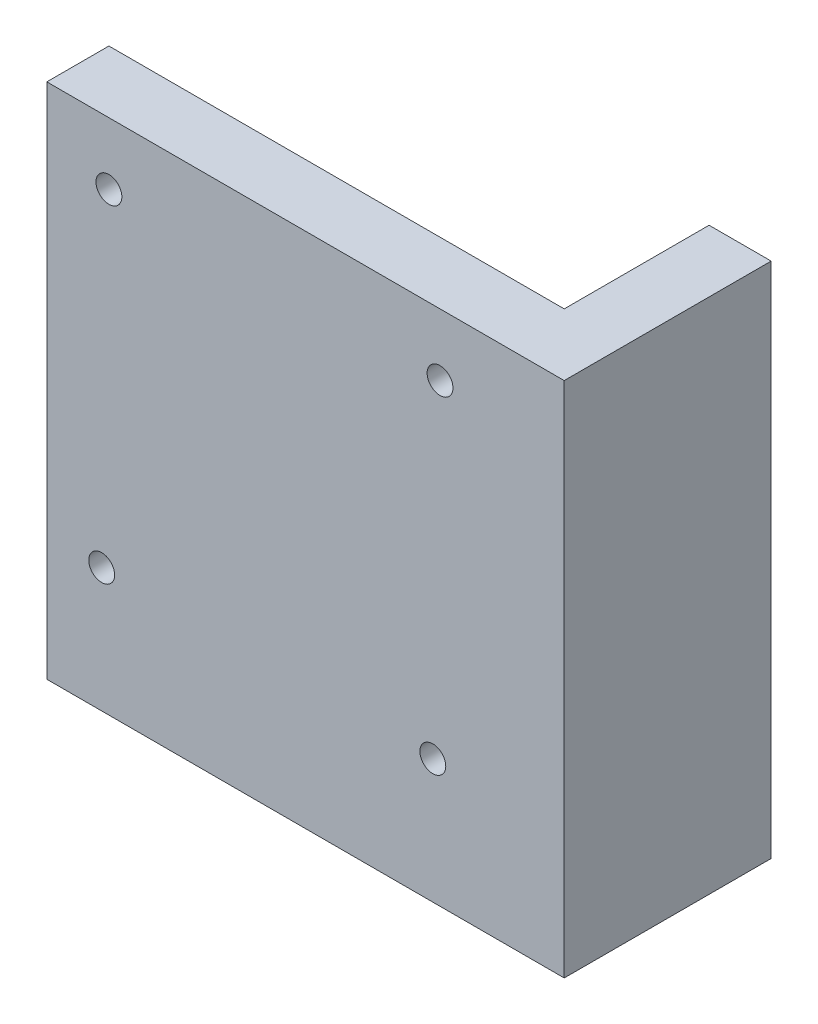
SolidWorks part; units mm, degrees
ref_plane "Front Plane" through (0, 0, 0) normal (0, 0, 1) x (1, 0, 0)
ref_plane "Top Plane" through (0, 0, 0) normal (0, 1, 0) x (1, 0, 0)
ref_plane "Right Plane" through (0, 0, 0) normal (1, 0, 0) x (0, 0, -1)
sketch "Sketch1" plane through (0, 0, 0) normal (0, 1, 0) x (1, 0, 0)
  line L1 (0, 0) -> (50, 0)
  line L2 (0, 0) -> (0, 20)
  line L3 (0, 20) -> (50, 20)
  line L4 (50, 0) -> (50, 20)
  dimension "D1" = 50
  dimension "D2" = 20
extrude "Boss-Extrude1" add sketch "Sketch1" along normal blind 6
sketch "Sketch2" plane through (0, 6, 0) normal (0, 1, 0) x (1, 0, 0)
  line L0 (50, 20) -> (0, 20) construction
  line L1 (50, 0) -> (44, 0)
  line L2 (50, 0) -> (50, 20)
  line L3 (50, 20) -> (44, 20)
  line L4 (44, 0) -> (44, 20)
  dimension "D1" = 6
extrude "Boss-Extrude2" add sketch "Sketch2" along normal blind 44
sketch "Sketch3" plane through (0, 6, 0) normal (0, 1, 0) x (1, 0, 0)
  line L0 (0, 20) -> (0, 0) construction
  line L1 (44, 0) -> (0, 0)
  line L2 (44, 0) -> (44, 6)
  line L3 (44, 6) -> (0, 6)
  line L4 (0, 0) -> (0, 6)
  dimension "D1" = 6
extrude "Boss-Extrude3" add sketch "Sketch3" along normal blind 44
sketch "Sketch5" plane through (0, 0, 0) normal (0, 0, 1) x (1, 0, 0)
  line L0 (0, 50) -> (50, 50) construction
  line L1 (0, 50) -> (0, 0) construction
  circle A0 centre (6, 44) radius 1.25
  circle A1 centre (38, 44) radius 1.25
  circle A2 centre (5.3024, 12) radius 1.25
  circle A3 centre (37.3024, 12) radius 1.25
  dimension "D1" = 6
  dimension "D2" = 6
  dimension "D3" = 32
  dimension "D4" = 32
  dimension "D5" = 32
  dimension "D6" = 38
  dimension "D7" = 6
extrude "Cut-Extrude1" cut sketch "Sketch5" against normal through all
